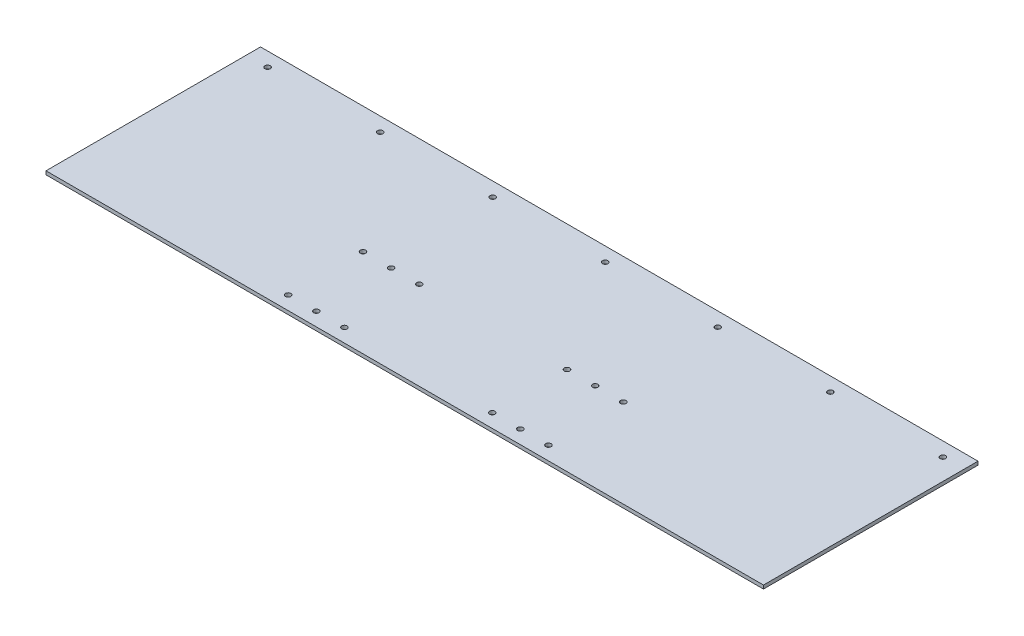
SolidWorks part; units mm, degrees
material "5052-H32"
ref_plane "Front" through (0, 0, 0) normal (0, 0, 1) x (1, 0, 0)
ref_plane "Top" through (0, 0, 0) normal (0, 1, 0) x (1, 0, 0)
ref_plane "Right" through (0, 0, 0) normal (1, 0, 0) x (0, 0, -1)
sketch "Sketch1" plane through (0, 0, 0) normal (0, 1, 0) x (1, 0, 0)
  line L0 (231.775, 0) -> (231.775, 46.0375) construction
  line L1 (0, 0) -> (647.7, 0)
  line L2 (0, 0) -> (0, 193.675)
  line L3 (0, 193.675) -> (647.7, 193.675)
  line L4 (647.7, 0) -> (647.7, 193.675)
  line L5 (231.775, 46.0375) -> (253.2062, 46.0375) construction
  line L6 (206.375, 12.2555) -> (257.175, 12.2555) construction
  line L7 (206.375, 79.8195) -> (257.175, 79.8195) construction
  line L8 (323.85, 193.675) -> (323.85, 180.975) construction
  line L9 (441.325, 79.8195) -> (390.525, 79.8195) construction
  line L10 (441.325, 12.2555) -> (390.525, 12.2555) construction
  line L11 (415.925, 46.0375) -> (394.4937, 46.0375) construction
  line L12 (415.925, 0) -> (415.925, 46.0375) construction
  circle A0 centre (231.775, 46.0375) radius 21.4312 construction
  circle A1 centre (231.775, 12.2555) radius 2.4257
  circle A2 centre (257.175, 12.2555) radius 2.4257
  circle A3 centre (206.375, 12.2555) radius 2.4257
  circle A4 centre (257.175, 79.8195) radius 2.4257
  circle A5 centre (231.775, 79.8195) radius 2.4257
  circle A6 centre (206.375, 79.8195) radius 2.4257
  circle A7 centre (323.85, 180.975) radius 2.4257
  circle A8 centre (425.45, 180.975) radius 2.4257
  circle A9 centre (527.05, 180.975) radius 2.4257
  circle A12 centre (120.65, 180.975) radius 2.4257
  circle A13 centre (222.25, 180.975) radius 2.4257
  circle A14 centre (628.65, 180.975) radius 2.4257
  circle A15 centre (19.05, 180.975) radius 2.4257
  circle A16 centre (415.925, 46.0375) radius 21.4312 construction
  circle A17 centre (441.325, 79.8195) radius 2.4257
  circle A18 centre (415.925, 79.8195) radius 2.4257
  circle A19 centre (390.525, 79.8195) radius 2.4257
  circle A20 centre (441.325, 12.2555) radius 2.4257
  circle A21 centre (390.525, 12.2555) radius 2.4257
  circle A22 centre (415.925, 12.2555) radius 2.4257
  dimension "D3" = 42.8625
  dimension "D5" = 4.8514
  dimension "D9" = 4.8514
  dimension "D1" = 647.7
  dimension "D2" = 193.675
  dimension "D4" = 46.0375
  dimension "D6" = 33.782
  dimension "D7" = 25.4
  dimension "D8" = 12.7
  dimension "D11" = 101.6
  dimension "D12" = 231.775
  dimension "D10" = 4
extrude "Boss-Extrude1" add sketch "Sketch1" along normal blind 3.175
sketch "Sketch2" plane through (0, 3.175, 0) normal (0, 1, 0) x (1, 0, 0)
  line L0 (0, 193.675) -> (0, 0) construction
  line L1 (0, 0) -> (647.7, 0) construction
  line L2 (323.85, 193.675) -> (323.85, -51.395) construction
  line L3 (647.7, 193.675) -> (0, 193.675) construction
  circle A0 centre (6.35, 12.7) radius 2.4257
  circle A1 centre (6.35, 82.55) radius 2.4257
  circle A2 centre (6.35, 152.4) radius 2.4257
  circle A3 centre (6.35, 222.25) radius 2.4257
  circle A4 centre (641.35, 222.25) radius 2.4257
  circle A5 centre (641.35, 152.4) radius 2.4257
  circle A6 centre (641.35, 82.55) radius 2.4257
  circle A7 centre (641.35, 12.7) radius 2.4257
  dimension "D3" = 4.8514
  dimension "D1" = 6.35
  dimension "D2" = 12.7
  dimension "D5" = 69.85
  dimension "D4" = 4
extrude "Cut-Extrude1" [suppressed] cut sketch "Sketch2" against normal through all
fillet "Fillet1" [suppressed] radius 3.175
